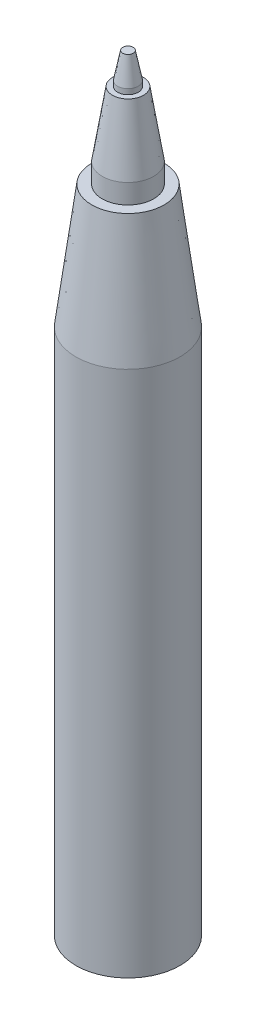
SolidWorks part; units mm, degrees
ref_plane "Front" through (0, 0, 0) normal (0, 0, 1) x (1, 0, 0)
ref_plane "Top" through (0, 0, 0) normal (0, 1, 0) x (1, 0, 0)
ref_plane "Right" through (0, 0, 0) normal (1, 0, 0) x (0, 0, -1)
sketch "Sketch1" plane through (0, 0, 0) normal (0, 0, 1) x (1, 0, 0)
  line L0 (0, 0.8393) -> (0, -0.8393) construction
  line L1 (0, 0) -> (4, 0)
  line L2 (4, 0) -> (4, 40.5)
  line L3 (4, 40.5) -> (2.7781, 50)
  line L4 (2.7781, 50) -> (1.9781, 50)
  line L5 (1.9781, 50) -> (1.9781, 51.5)
  line L6 (1.9781, 51.5) -> (1.1906, 56.5)
  line L7 (1.1906, 56.5) -> (0.7906, 56.5)
  line L8 (0.7906, 56.5) -> (0.7906, 56.9)
  line L9 (0.7906, 56.9) -> (0.4, 58.9)
  line L10 (0.4, 58.9) -> (0, 58.9)
  line L11 (0, 58.9) -> (0, 0)
  dimension "D1" = 8
  dimension "D2" = 0.8
  dimension "D3" = 0.4
  dimension "D4" = 5.5563
  dimension "D5" = 2.3813
  dimension "D6" = 0.8
  dimension "D7" = 50
  dimension "D8" = 9.5
  dimension "D9" = 1.5
  dimension "D10" = 5
  dimension "D11" = 0.4
  dimension "D12" = 2
revolve "Revolve1" add sketch "Sketch1" angle 360 about L0
